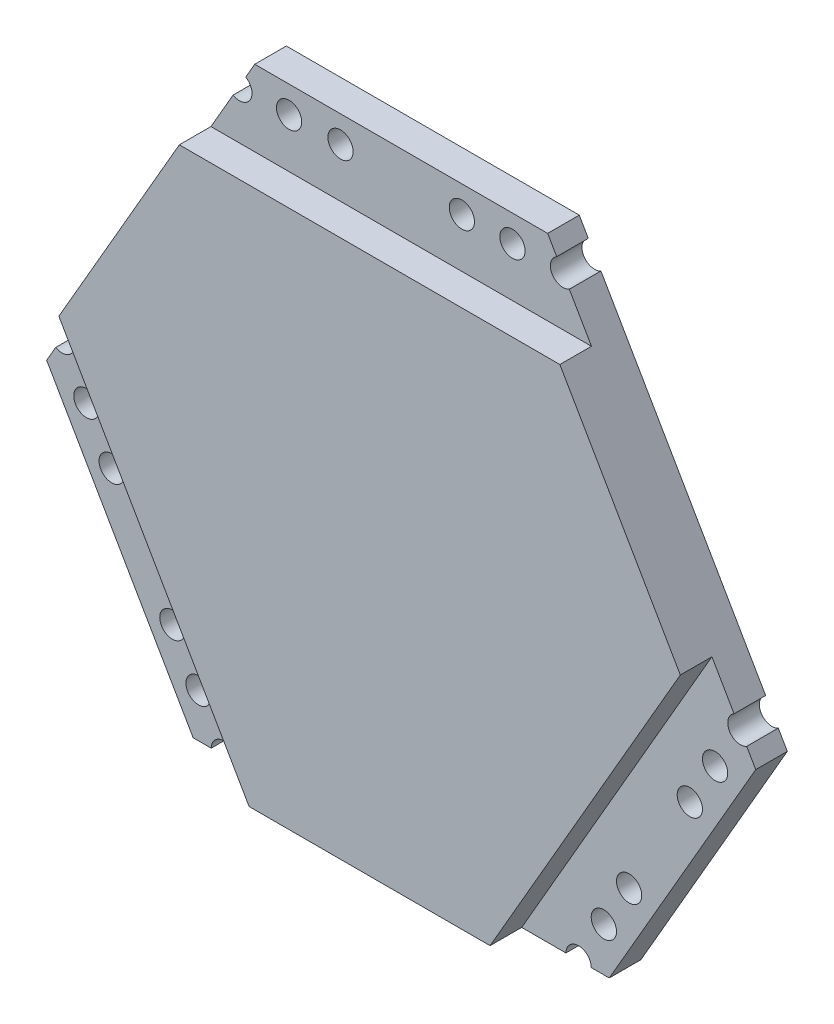
SolidWorks part; units mm, degrees
material "ABS"
ref_plane "前基準面" through (0, 0, 0) normal (0, 0, 1) x (1, 0, 0)
ref_plane "上基準面" through (0, 0, 0) normal (0, 1, 0) x (1, 0, 0)
ref_plane "右基準面" through (0, 0, 0) normal (1, 0, 0) x (0, 0, -1)
sketch "草圖1" plane through (0, 0, 0) normal (0, 0, 1) x (1, 0, 0)
  line L0 (29.3027, 33.7186) -> (37.3027, 33.7186) construction
  line L1 (45.3027, 33.7186) -> (-5.8973, 33.7186)
  line L2 (-5.8973, 33.7186) -> (-33.9573, -14.8827)
  line L3 (-33.9573, -14.8827) -> (-5.8973, 33.7186)
  line L7 (-33.9573, -14.8827) -> (-8.3573, -59.2232)
  line L8 (-8.3573, -59.2232) -> (-33.9573, -14.8827)
  line L9 (-8.3573, -59.2232) -> (47.7627, -59.2232)
  line L10 (47.7627, -59.2232) -> (73.3627, -14.8827)
  line L11 (73.3627, -14.8827) -> (45.3027, 33.7186)
  line L12 (73.3627, -14.8827) -> (69.3627, -21.8109) construction
  line L13 (-10.3973, 37.9244) -> (49.8027, 37.9244)
  line L14 (-10.3973, 37.9244) -> (-10.3973, 25.9244)
  line L15 (-10.3973, 25.9244) -> (49.8027, 25.9244)
  line L16 (49.8027, 37.9244) -> (49.8027, 25.9244)
  line L17 (-29.4573, -7.0885) -> (0.6427, -59.2232)
  line L18 (0.6427, -59.2232) -> (-9.7496, -65.2232)
  line L19 (-9.7496, -65.2232) -> (-39.8496, -13.0885)
  line L20 (-39.8496, -13.0885) -> (-29.4573, -7.0885)
  line L21 (55.7627, -45.3668) -> (51.7627, -52.295) construction
  line L22 (68.8627, -7.0885) -> (38.7627, -59.2232)
  line L23 (38.7627, -59.2232) -> (49.155, -65.2232)
  line L24 (49.155, -65.2232) -> (79.255, -13.0885)
  line L25 (79.255, -13.0885) -> (68.8627, -7.0885)
  circle A0 centre (-5.8973, 33.7186) radius 2
  circle A1 centre (1.9623, 33.7186) radius 2
  circle A2 centre (10.1027, 33.7186) radius 2
  circle A4 centre (29.3027, 33.7186) radius 2
  circle A8 centre (-33.9573, -14.8827) radius 2
  circle A9 centre (-30.0977, -21.8109) radius 2
  circle A10 centre (-26.0977, -28.7391) radius 2
  circle A12 centre (-16.4977, -45.3668) radius 2
  circle A13 centre (-12.3573, -52.295) radius 2
  circle A14 centre (-8.3573, -59.2232) radius 2
  circle A15 centre (47.7627, -59.2232) radius 2
  circle A18 centre (55.7627, -45.3668) radius 2
  circle A22 centre (37.3027, 33.7186) radius 2
  circle A23 centre (45.3027, 33.7186) radius 2
  circle A24 centre (73.3627, -14.8827) radius 2
  circle A25 centre (69.3627, -21.8109) radius 2
  circle A26 centre (65.3627, -28.7391) radius 2
  circle A27 centre (51.7627, -52.295) radius 2
  dimension "D1" = 4
  dimension "D6" = 4
  dimension "D10" = 4
  dimension "D13" = 19.2
  dimension "D11" = 4
  dimension "D15" = 19.2
  dimension "D7" = 19.2
  dimension "D17" = 8
  dimension "D2" = 8
  dimension "D3" = 120
  dimension "D4" = 120
  dimension "D5" = 56.12
  dimension "D8" = 120
  dimension "D9" = 56.12
  dimension "D12" = 8
  dimension "D16" = 56.12
  dimension "D18" = 4.5
  dimension "D19" = 4.5
  dimension "D20" = 60.2
  dimension "D21" = 12
  dimension "D22" = 90
  dimension "D23" = 180
  dimension "D24" = 12
  dimension "D25" = 4.5
  dimension "D26" = 4.5
  dimension "D27" = 8
  dimension "D28" = 12
  dimension "D29" = 60.2
  dimension "D30" = 90
  dimension "D31" = 4.5
  dimension "D14" = 3
extrude "填料-伸長4" add sketch "草圖1" along normal blind 10 contours L22 L11 L15 L3 L17 L9 | A23 L1 A22 A4 A2 A1 A0 L3 L15 L11 | A23 L11 L16 L13 L14 L3 A0 L1 A1 A2 A4 A22 | A14 L8 A13 A12 A10 A9 A8 L2 L20 L19 L18 L9 | A14 L9 L17 L2 A8 L8 A9 A10 A12 A13 | A27 L10 A15 L9 L23 L24 L25 L11 A24 A25 A26 A18 | A27 L10 A18 A26 A25 A24 L11 L22 L9 A15
sketch "草圖4" plane through (0, 0, 10) normal (0, 0, 1) x (1, 0, 0)
  line L0 (38.7627, -59.2232) -> (49.155, -65.2232)
  line L1 (-10.3973, 37.9244) -> (49.8027, 37.9244)
  line L2 (-10.3973, 37.9244) -> (-10.3973, 25.9244)
  line L3 (-10.3973, 25.9244) -> (49.8027, 25.9244)
  line L4 (49.8027, 37.9244) -> (49.8027, 25.9244)
  line L5 (38.7627, -59.2232) -> (68.8722, -7.072)
  line L6 (49.155, -65.2232) -> (79.2645, -13.072)
  line L7 (68.8722, -7.072) -> (79.2645, -13.072)
  line L8 (-29.4573, -7.0885) -> (-39.8496, -13.0885)
  line L9 (-29.4573, -7.0885) -> (0.9201, -59.7038)
  line L10 (-39.8496, -13.0885) -> (-9.4722, -65.7038)
  line L11 (0.9201, -59.7038) -> (-9.4722, -65.7038)
extrude "除料-伸長2" cut sketch "草圖4" against normal blind 5
sketch "草圖7" plane through (-19.0236, 10.9833, 0) normal (-0.866, 0.5, 0) x (0, 0, 1)
  line L0 (0, -5.7866) -> (10, -5.7866)
  line L1 (0, -5.7866) -> (0, 46.268)
  line L2 (10, -5.7866) -> (10, 46.268)
  line L3 (0, 46.268) -> (10, 46.268)
  line L4 (0, 17.2525) -> (0, -20.8675) construction
  line L5 (10, 17.2525) -> (10, -20.8675) construction
  line L6 (0, -5.7866) -> (10, -5.7866)
  line L7 (0, -5.7866) -> (0, -53.8162)
  line L8 (10, -5.7866) -> (10, -53.8162)
  line L9 (0, -53.8162) -> (10, -53.8162)
  line M2 (0, -20.8675) -> (5, -20.8675)
  line M3 (5, -20.8675) -> (10, -20.8675)
  line M5 (10, 17.2525) -> (5, 17.2525)
  line M6 (5, 17.2525) -> (0, 17.2525)
extrude "除料-伸長9" cut sketch "草圖7" along direction (-0.866, 0.5, 0) on the side of the normal through all contours L7 L9 L8 M3 M2 | L3 L1 L2 M6 M5
sketch "草圖12" plane through (48.5776, 28.0463, 0) normal (0.866, 0.5, 0) x (0, 0, -1)
  line L0 (0, -23.6856) -> (-10, -23.6856)
  line L1 (0, -23.6856) -> (0, -70.3801)
  line L2 (-10, -23.6856) -> (-10, -70.3801)
  line L3 (0, -70.3801) -> (-10, -70.3801)
  line L4 (0, -40.5702) -> (0, -2.4502) construction
  line L5 (-10, -40.5702) -> (-10, -2.4502) construction
  line L6 (0, -23.6856) -> (-10, -23.6856)
  line L7 (0, -23.6856) -> (0, 27.878)
  line L8 (-10, -23.6856) -> (-10, 27.878)
  line L9 (0, 27.878) -> (-10, 27.878)
  line M2 (0, -2.4502) -> (-5, -2.4502)
  line M3 (-5, -2.4502) -> (-10, -2.4502)
  line M5 (-10, -40.5702) -> (-5, -40.5702)
  line M6 (-5, -40.5702) -> (0, -40.5702)
extrude "除料-伸長12" cut sketch "草圖12" along normal through all contours L3 L1 L2 M6 M5 | L7 L9 L8 M3 M2
sketch "草圖13" plane through (0, -59.2232, 0) normal (0, -1, 0) x (1, 0, 0)
  line L0 (19.7027, 10) -> (19.7027, 0)
  line L1 (19.7027, 10) -> (-25.3386, 10)
  line L2 (19.7027, 0) -> (-25.3386, 0)
  line L3 (-25.3386, 10) -> (-25.3386, 0)
  line L4 (0.6427, 10) -> (38.7627, 10) construction
  line L5 (0.6427, 0) -> (38.7627, 0) construction
  line L6 (19.7027, 10) -> (19.7027, 0)
  line L7 (19.7027, 10) -> (66.2602, 10)
  line L8 (19.7027, 0) -> (66.2602, 0)
  line L9 (66.2602, 10) -> (66.2602, 0)
  line M2 (38.7627, 0) -> (38.7627, 5)
  line M3 (38.7627, 5) -> (38.7627, 10)
  line M5 (0.6427, 10) -> (0.6427, 5)
  line M6 (0.6427, 5) -> (0.6427, 0)
extrude "除料-伸長13" cut sketch "草圖13" along normal through all contours L9 L7 L8 M3 M2 | L1 L3 L2 M6 M5
sketch "草圖17" plane through (0, 0, 0) normal (0, 0, -1) x (-1, 0, 0)
  text T0 "Buttom" font "Impact" height in points 26
extrude "除料-伸長15" cut sketch "草圖17" against normal blind 2
